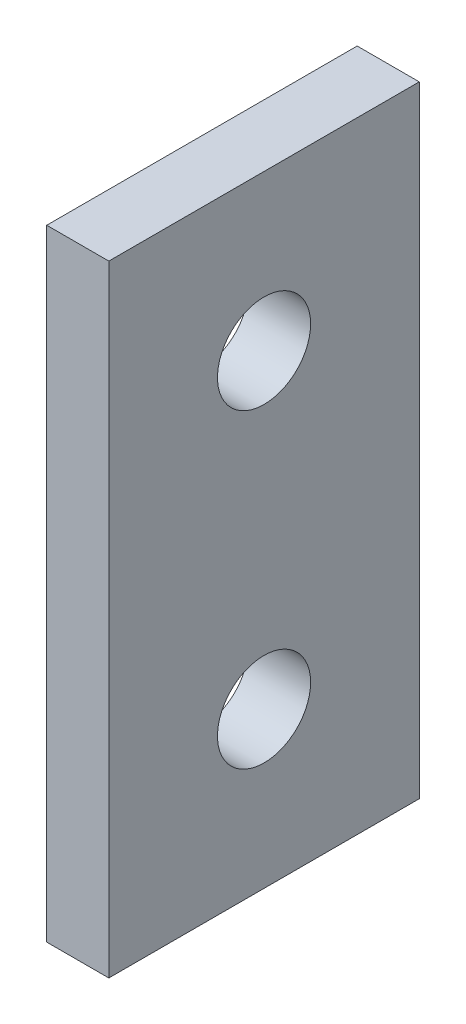
SolidWorks part; units mm, degrees
material "Perspex (TM) GS Acrylic Cast Sheet"
ref_plane "Front Plane" through (0, 0, 0) normal (0, 0, 1) x (1, 0, 0)
ref_plane "Top Plane" through (0, 0, 0) normal (0, 1, 0) x (1, 0, 0)
ref_plane "Right Plane" through (0, 0, 0) normal (1, 0, 0) x (0, 0, -1)
sketch "Sketch1" plane through (0, 0, 0) normal (1, 0, 0) x (0, 0, -1)
  line L0 (0, 55) -> (0, -55) construction
  line L1 (-5, 10) -> (5, 10)
  line L2 (-5, 10) -> (-5, -10)
  line L3 (-5, -10) -> (5, -10)
  line L4 (5, 10) -> (5, -10)
  line L5 (-5, 10) -> (5, -10) construction
  line L6 (-5, -10) -> (5, 10) construction
  line L7 (55, 0) -> (-55, 0) construction
  circle A0 centre (0, 5) radius 1.5
  circle A1 centre (0, -5) radius 1.5
  point P0 (0, 0)
  dimension "D1" = 3
  dimension "D3" = 10
  dimension "D4" = 5
  dimension "D2" = 10
  dimension "D5" = 20
extrude "Boss-Extrude1" add sketch "Sketch1" along normal blind 2
